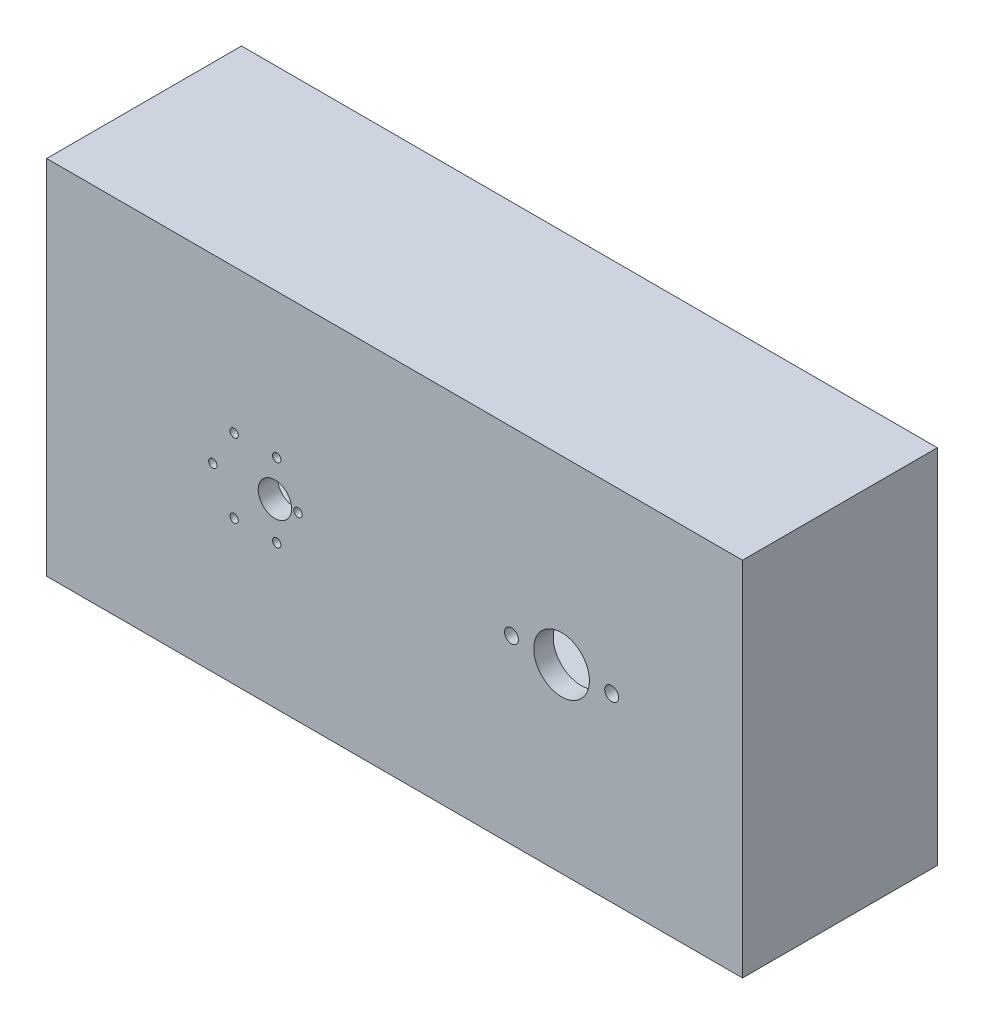
SolidWorks part; units mm, degrees
ref_plane "Front Plane" through (0, 0, 0) normal (0, 0, 1) x (1, 0, 0)
ref_plane "Top Plane" through (0, 0, 0) normal (0, 1, 0) x (1, 0, 0)
ref_plane "Right Plane" through (0, 0, 0) normal (1, 0, 0) x (0, 0, -1)
sketch "Sketch1" plane through (0, 0, 0) normal (0, 0, 1) x (1, 0, 0)
  line L1 (-125, 65) -> (125, 65)
  line L2 (-125, 65) -> (-125, -65)
  line L3 (-125, -65) -> (125, -65)
  line L4 (125, 65) -> (125, -65)
  line L5 (-125, 65) -> (125, -65) construction
  line L6 (-125, -65) -> (125, 65) construction
  point P0 (0, 0)
  dimension "D1" = 130
  dimension "D2" = 250
extrude "Boss-Extrude1" add sketch "Sketch1" along normal blind 70
shell "Shell1" thickness 7
sketch "Sketch2" plane through (0, 0, 70) normal (0, 0, 1) x (1, 0, 0)
  line L0 (125, -65) -> (125, 65) construction
  line L1 (-125, -65) -> (125, -65) construction
  line L2 (-125, 0) -> (125, 0) construction
  line L3 (-125, 65) -> (-125, -65) construction
  circle A0 centre (60, 0) radius 10
  circle A6 centre (42, 0) radius 2.5
  circle A7 centre (78, 0) radius 2.5
  circle A10 centre (-34.7, 0) radius 1.5
  circle A11 centre (-42.35, -13.2502) radius 1.5
  circle A12 centre (-57.65, -13.2502) radius 1.5
  circle A13 centre (-65.3, 0) radius 1.5
  circle A14 centre (-57.65, 13.2502) radius 1.5
  circle A15 centre (-42.35, 13.2502) radius 1.5
  circle A16 centre (-43, 0) radius 6
  point P33 (-50, 0)
  dimension "D1" = 20
  dimension "D4" = 103
  dimension "D7" = 3
  dimension "D10" = 5
  dimension "D11" = 5
  dimension "D6" = 8.3
  dimension "D15" = 12
  dimension "D2" = 65
  dimension "D3" = 65
  dimension "D5" = 22.3
  dimension "D9" = 6
  dimension "D12" = 18
  dimension "D13" = 18
  dimension "D14" = 13.2502
extrude "Cut-Extrude1" cut sketch "Sketch2" against normal blind 90
